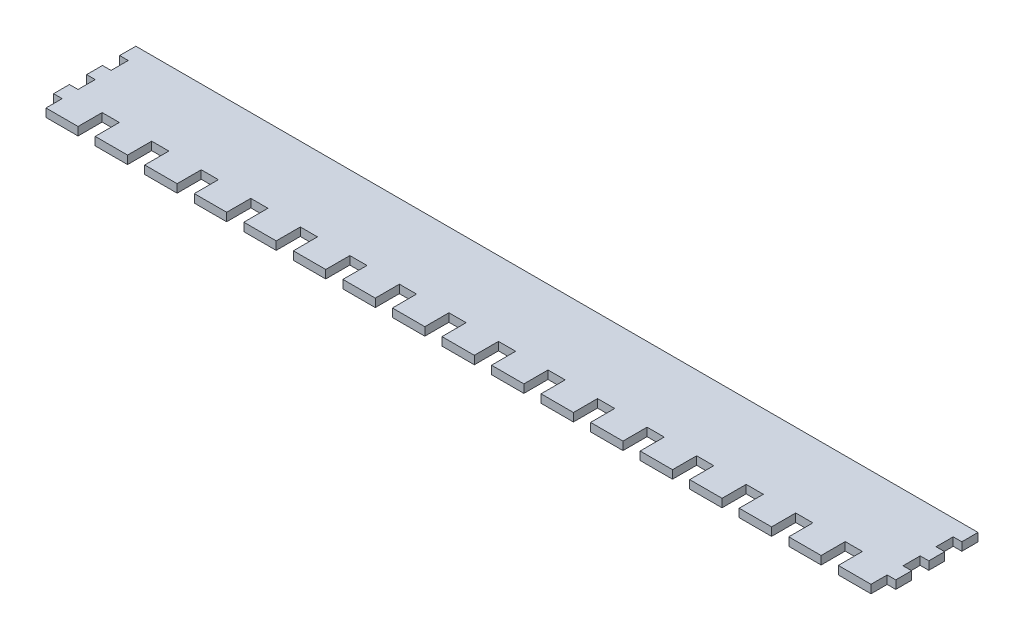
SolidWorks part; units mm, degrees
ref_plane "Front Plane" through (0, 0, 0) normal (0, 0, 1) x (1, 0, 0)
ref_plane "Top Plane" through (0, 0, 0) normal (0, 1, 0) x (1, 0, 0)
ref_plane "Right Plane" through (0, 0, 0) normal (1, 0, 0) x (0, 0, -1)
sketch "Sketch1" plane through (0, 0, 0) normal (0, 1, 0) x (1, 0, 0)
  line L2 (-323.85, -28.575) -> (-323.85, 28.575)
  line L3 (-323.85, 28.575) -> (323.85, 28.575)
  line L4 (323.85, -28.575) -> (323.85, 28.575)
  line L5 (-323.85, -28.575) -> (323.85, 28.575) construction
  line L6 (-323.85, 28.575) -> (323.85, -28.575) construction
  line L11 (-323.85, -28.575) -> (323.85, -28.575)
  point P0 (0, 0)
  dimension "D1" = 57.15
  dimension "D2" = 647.7
extrude "Boss-Extrude1" add sketch "Sketch1" along normal blind 6.35
sketch "Sketch3" plane through (0, 0, 0) normal (0, 1, 0) x (1, 0, 0)
  line L0 (-323.85, -28.575) -> (323.85, -28.575) construction
  line L2 (-317.5, -47.117) -> (-292.608, -47.117)
  line L3 (-292.608, -47.117) -> (-292.608, -28.575)
  line L4 (-292.608, -28.575) -> (-317.5, -28.575)
  line L25 (-254.508, -47.117) -> (-254.508, -28.575)
  line L26 (-254.508, -28.575) -> (-279.4, -28.575)
  line L27 (-279.4, -28.575) -> (-279.4, -47.117)
  line L28 (-279.4, -47.117) -> (-254.508, -47.117)
  line L29 (-216.408, -47.117) -> (-216.408, -28.575)
  line L30 (-216.408, -28.575) -> (-241.3, -28.575)
  line L31 (-241.3, -28.575) -> (-241.3, -47.117)
  line L32 (-241.3, -47.117) -> (-216.408, -47.117)
  line L33 (-178.308, -47.117) -> (-178.308, -28.575)
  line L34 (-178.308, -28.575) -> (-203.2, -28.575)
  line L35 (-203.2, -28.575) -> (-203.2, -47.117)
  line L36 (-203.2, -47.117) -> (-178.308, -47.117)
  line L37 (-140.208, -47.117) -> (-140.208, -28.575)
  line L38 (-140.208, -28.575) -> (-165.1, -28.575)
  line L39 (-165.1, -28.575) -> (-165.1, -47.117)
  line L40 (-165.1, -47.117) -> (-140.208, -47.117)
  line L41 (-102.108, -47.117) -> (-102.108, -28.575)
  line L42 (-102.108, -28.575) -> (-127, -28.575)
  line L43 (-127, -28.575) -> (-127, -47.117)
  line L44 (-127, -47.117) -> (-102.108, -47.117)
  line L45 (-64.008, -47.117) -> (-64.008, -28.575)
  line L46 (-64.008, -28.575) -> (-88.9, -28.575)
  line L47 (-88.9, -28.575) -> (-88.9, -47.117)
  line L48 (-88.9, -47.117) -> (-64.008, -47.117)
  line L49 (-25.908, -47.117) -> (-25.908, -28.575)
  line L50 (-25.908, -28.575) -> (-50.8, -28.575)
  line L51 (-50.8, -28.575) -> (-50.8, -47.117)
  line L52 (-50.8, -47.117) -> (-25.908, -47.117)
  line L53 (12.192, -47.117) -> (12.192, -28.575)
  line L54 (12.192, -28.575) -> (-12.7, -28.575)
  line L55 (-12.7, -28.575) -> (-12.7, -47.117)
  line L56 (-12.7, -47.117) -> (12.192, -47.117)
  line L57 (50.292, -47.117) -> (50.292, -28.575)
  line L58 (50.292, -28.575) -> (25.4, -28.575)
  line L59 (25.4, -28.575) -> (25.4, -47.117)
  line L60 (25.4, -47.117) -> (50.292, -47.117)
  line L61 (88.392, -47.117) -> (88.392, -28.575)
  line L62 (88.392, -28.575) -> (63.5, -28.575)
  line L63 (63.5, -28.575) -> (63.5, -47.117)
  line L64 (63.5, -47.117) -> (88.392, -47.117)
  line L65 (126.492, -47.117) -> (126.492, -28.575)
  line L66 (126.492, -28.575) -> (101.6, -28.575)
  line L67 (101.6, -28.575) -> (101.6, -47.117)
  line L68 (101.6, -47.117) -> (126.492, -47.117)
  line L69 (164.592, -47.117) -> (164.592, -28.575)
  line L70 (164.592, -28.575) -> (139.7, -28.575)
  line L71 (139.7, -28.575) -> (139.7, -47.117)
  line L72 (139.7, -47.117) -> (164.592, -47.117)
  line L73 (202.692, -47.117) -> (202.692, -28.575)
  line L74 (202.692, -28.575) -> (177.8, -28.575)
  line L75 (177.8, -28.575) -> (177.8, -47.117)
  line L76 (177.8, -47.117) -> (202.692, -47.117)
  line L77 (240.792, -47.117) -> (240.792, -28.575)
  line L78 (240.792, -28.575) -> (215.9, -28.575)
  line L79 (215.9, -28.575) -> (215.9, -47.117)
  line L80 (215.9, -47.117) -> (240.792, -47.117)
  line L81 (278.892, -47.117) -> (278.892, -28.575)
  line L82 (278.892, -28.575) -> (254, -28.575)
  line L83 (254, -28.575) -> (254, -47.117)
  line L84 (254, -47.117) -> (278.892, -47.117)
  line L87 (316.992, -28.575) -> (292.1, -28.575)
  line L88 (292.1, -28.575) -> (292.1, -47.117)
  line L89 (292.1, -47.117) -> (316.992, -47.117)
  line L91 (-323.85, -28.575) -> (-323.85, -47.117)
  line L92 (-323.85, -47.117) -> (-317.5, -47.117)
  line L93 (316.992, -47.117) -> (323.85, -47.117)
  line L94 (323.85, -47.117) -> (323.85, -28.575)
  line L95 (323.85, -28.575) -> (316.992, -28.575)
  line L96 (-323.85, -28.575) -> (-317.5, -28.575)
  line L97 (316.992, -47.117) -> (316.992, -28.575) [skipped]
  point P0 (-305.054, -28.575)
  dimension "D1" = 24.892
  dimension "D2" = 18.542
  dimension "D4" = 17
extrude "Boss-Extrude2" add sketch "Sketch3" along normal blind 6.35
sketch "Sketch4" plane through (0, 0, 0) normal (0, 1, 0) x (1, 0, 0)
  line L0 (-323.85, 28.575) -> (-323.85, -47.117) construction
  line L1 (323.85, 28.575) -> (-323.85, 28.575) construction
  line L2 (-330.454, 16.129) -> (-317.246, 16.129)
  line L3 (-330.454, 16.129) -> (-330.454, 2.921)
  line L4 (-330.454, 2.921) -> (-317.246, 2.921)
  line L5 (-317.246, 16.129) -> (-317.246, 2.921)
  line L6 (-330.454, 16.129) -> (-317.246, 2.921) construction
  line L7 (-330.454, 2.921) -> (-317.246, 16.129) construction
  line L8 (0, 0) -> (0, 63.6475) construction
  line L9 (-330.454, -9.271) -> (-317.246, -9.271)
  line L10 (-317.246, -9.271) -> (-317.246, -22.479)
  line L11 (-330.454, -22.479) -> (-317.246, -22.479)
  line L12 (-330.454, -9.271) -> (-330.454, -22.479)
  line L13 (330.454, 2.921) -> (317.246, 16.129) construction
  line L14 (330.454, 16.129) -> (317.246, 2.921) construction
  line L15 (330.454, -9.271) -> (330.454, -22.479)
  line L16 (330.454, -22.479) -> (317.246, -22.479)
  line L17 (317.246, -9.271) -> (317.246, -22.479)
  line L18 (330.454, -9.271) -> (317.246, -9.271)
  line L19 (317.246, 16.129) -> (317.246, 2.921)
  line L20 (330.454, 2.921) -> (317.246, 2.921)
  line L21 (330.454, 16.129) -> (330.454, 2.921)
  line L22 (330.454, 16.129) -> (317.246, 16.129)
  line L23 (-330.454, -34.671) -> (-317.246, -34.671)
  line L24 (-317.246, -34.671) -> (-317.246, -47.879)
  line L25 (-330.454, -47.879) -> (-317.246, -47.879)
  line L26 (-330.454, -34.671) -> (-330.454, -47.879)
  line L27 (330.454, -34.671) -> (330.454, -47.879)
  line L28 (330.454, -47.879) -> (317.246, -47.879)
  line L29 (317.246, -34.671) -> (317.246, -47.879)
  line L30 (330.454, -34.671) -> (317.246, -34.671)
  point P0 (-323.85, 9.525)
  point P1 (-323.85, 9.525)
  point P25 (323.85, 9.525)
  dimension "D1" = 13.208
  dimension "D2" = 13.208
  dimension "D3" = 19.05
  dimension "D5" = 3
extrude "Cut-Extrude2" cut sketch "Sketch4" along normal through all
